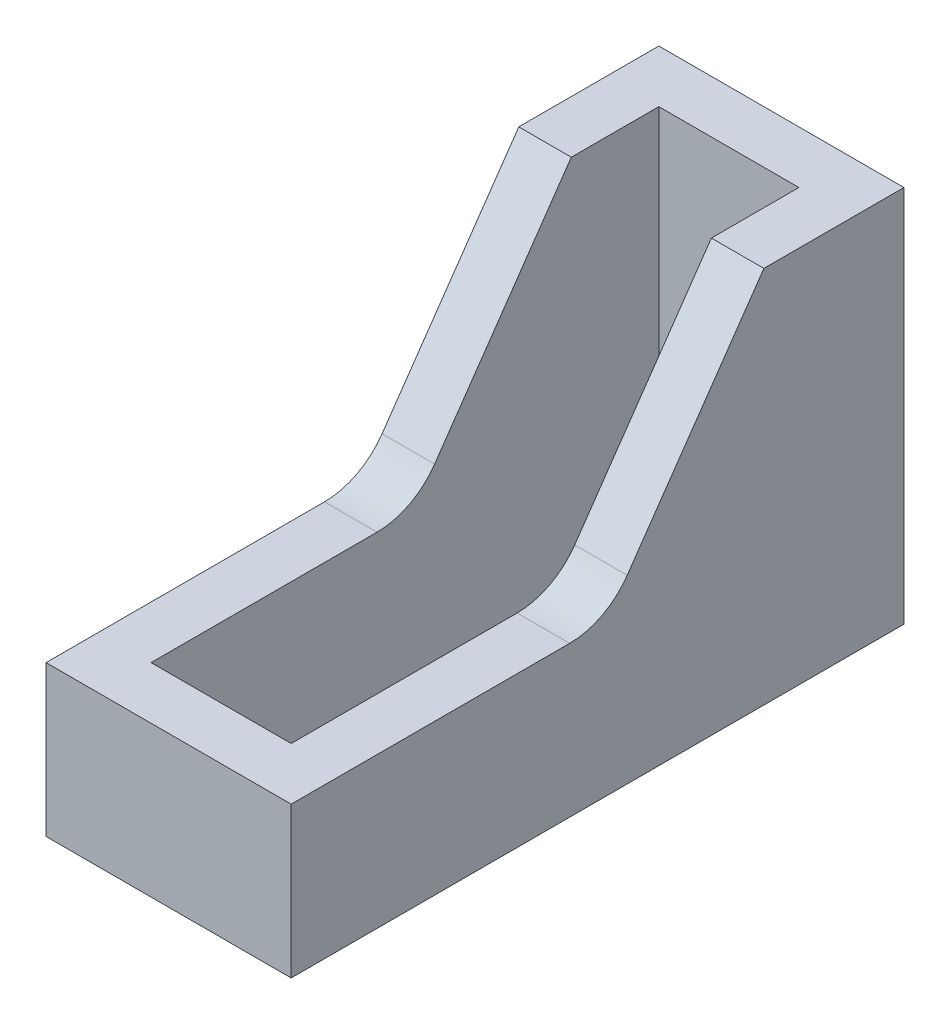
SolidWorks part; units mm, degrees
ref_plane "Alzado" through (0, 0, 0) normal (0, 0, 1) x (1, 0, 0)
ref_plane "Planta" through (0, 0, 0) normal (0, 1, 0) x (1, 0, 0)
ref_plane "Vista lateral" through (0, 0, 0) normal (1, 0, 0) x (0, 0, -1)
sketch "Croquis1" plane through (0, 0, 0) normal (0, 0, 1) x (1, 0, 0)
  line L1 (0, 0) -> (7, 0)
  line L2 (0, 0) -> (0, 10.8)
  line L3 (0, 10.8) -> (7, 10.8)
  line L4 (7, 0) -> (7, 10.8)
extrude "Saliente-Extruir1" add sketch "Croquis1" along normal blind 17.5
sketch "Croquis4" plane through (0, 10.8, 0) normal (0, 1, 0) x (1, 0, 0)
  line L9 (5, -16) -> (1.5, -16)
  line L10 (5, -16) -> (5, -1.5)
  line L11 (5, -1.5) -> (1.5, -1.5)
  line L12 (1.5, -16) -> (1.5, -1.5)
extrude "Cortar-Extruir1" cut sketch "Croquis4" against normal blind 17.5
sketch "Croquis5" plane through (7, 0, 0) normal (1, 0, 0) x (0, 0, -1)
  line L0 (0, 10.8) -> (7.8552, 27.8709)
  line L2 (-17.5, 0) -> (-17.5, 4.3)
  line L3 (-17.5, 0) -> (-17.5, 10.8) construction
  line L4 (-17.5, 4.3) -> (-9.5479, 4.3)
  line L8 (-7.9035, 5.1616) -> (8.0277, 28.1733)
  arc A0 (8.0277, 28.1733) -> (7.8552, 27.8709) centre (9.672, 27.0349) cw
  arc A1 (-9.5479, 4.3) -> (-7.9035, 5.1616) centre (-9.5479, 6.3) ccw
  dimension "D1" = 2
  dimension "D2" = 2
extrude "Cortar-Extruir2" cut sketch "Croquis5" along normal through all and the other way through all
sketch "Croquis6" plane through (0, 10.8, 0) normal (0, 1, 0) x (1, 0, 0)
  line L3 (1.5, -1.5) -> (5.5, -1.5)
  line L4 (1.5, -1.5) -> (1.5, -16)
  line L5 (1.5, -16) -> (5.5, -16)
  line L6 (5.5, -1.5) -> (5.5, -16)
extrude "Cortar-Extruir3" cut sketch "Croquis6" against normal blind 17.5
